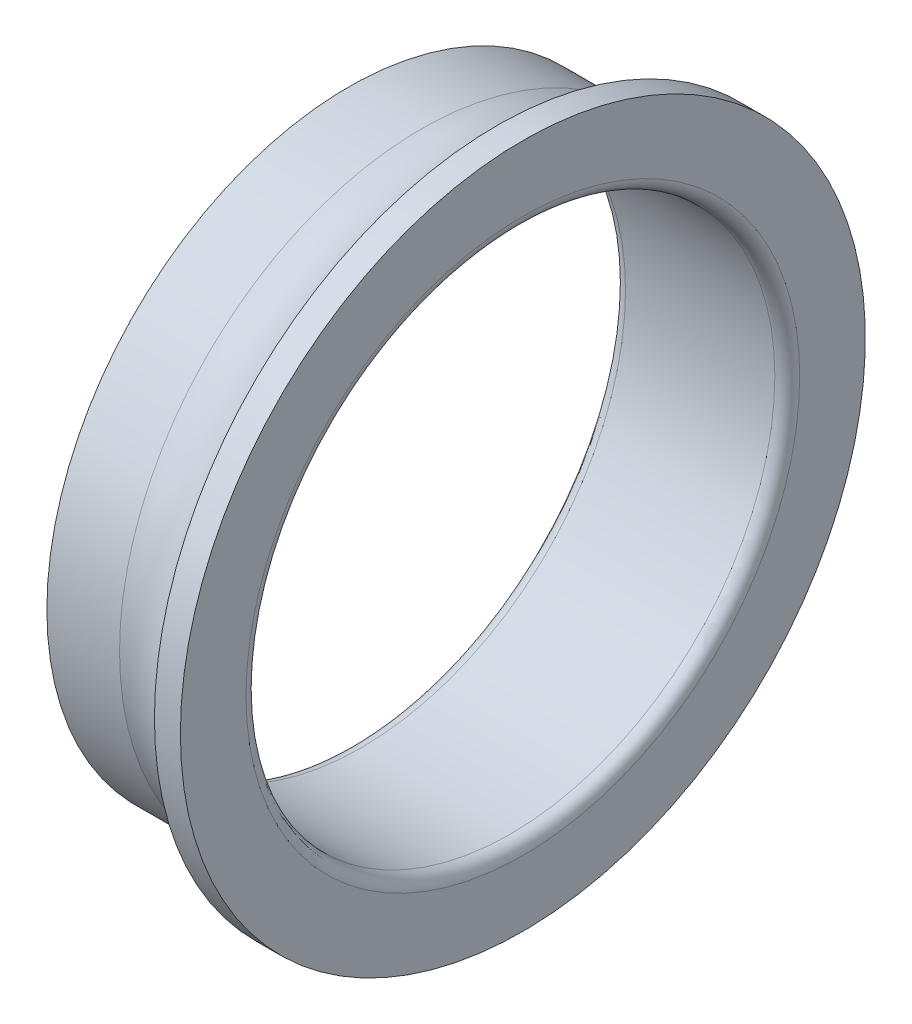
SolidWorks part; units mm, degrees
ref_plane "Piano frontale" through (0, 0, 0) normal (0, 0, 1) x (1, 0, 0)
ref_plane "Piano superiore" through (0, 0, 0) normal (0, 1, 0) x (1, 0, 0)
ref_plane "Piano destro" through (0, 0, 0) normal (1, 0, 0) x (0, 0, -1)
ref_plane "Piano1" through (0, 0, 0) normal (0, 0, 1) x (1, 0, 0)
sketch "Schizzo1" plane through (0, 0, 0) normal (0, 0, 1) x (1, 0, 0)
  line L0 (0, 48.51) -> (0, 44.5)
  line L1 (2, 42.5) -> (26, 42.5)
  line L2 (28, 44.5) -> (28, 55.05)
  line L3 (28, 55.05) -> (23.8265, 55.05)
  line L4 (11.6778, 48.51) -> (0, 48.51)
  line L5 (28, 0) -> (0, 0) construction
  arc A0 (0, 44.5) -> (2, 42.5) centre (2, 44.5) ccw
  arc A1 (26, 42.5) -> (28, 44.5) centre (26, 44.5) ccw
  arc A2 (23.8265, 55.05) -> (11.6778, 48.51) centre (14, 58.75) cw
revolve "Rivoluzione1" add sketch "Schizzo1" angle 360 about L5
